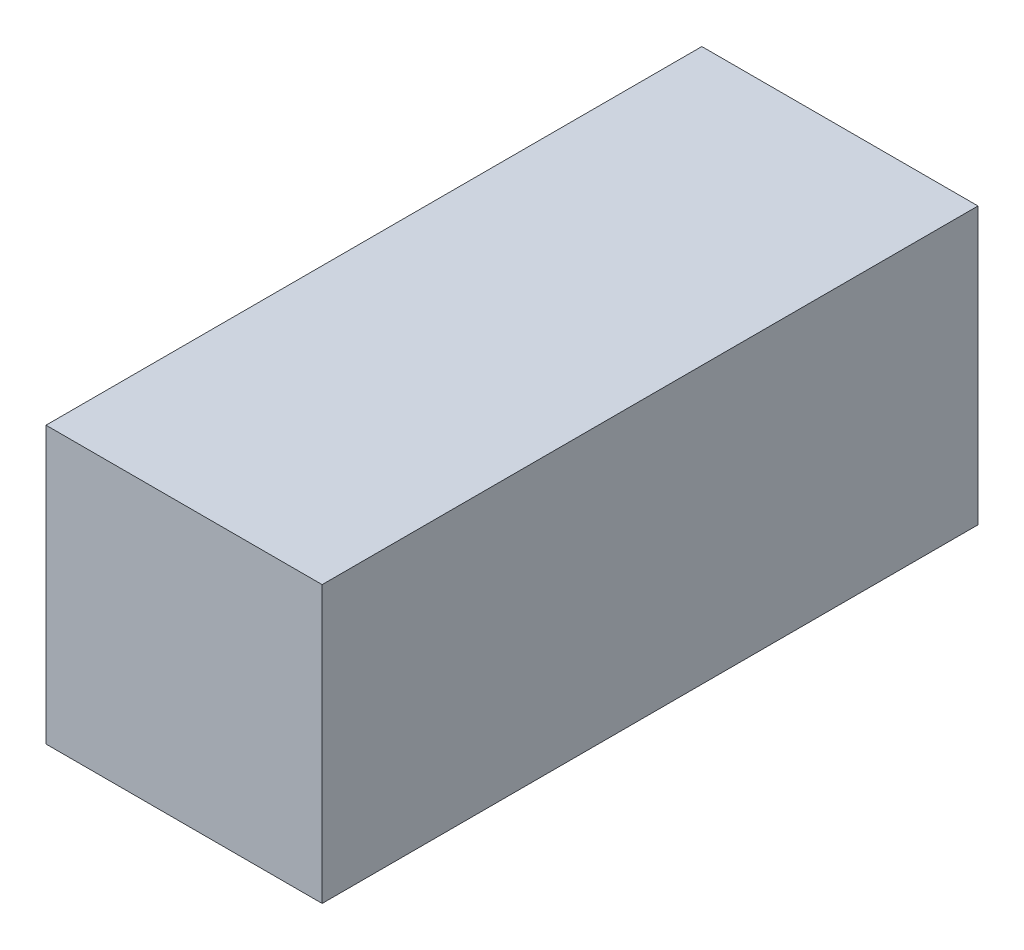
SolidWorks part; units mm, degrees
material "Cast Alloy Steel"
ref_plane "Front Plane" through (0, 0, 0) normal (0, 0, 1) x (1, 0, 0)
ref_plane "Top Plane" through (0, 0, 0) normal (0, 1, 0) x (1, 0, 0)
ref_plane "Right Plane" through (0, 0, 0) normal (1, 0, 0) x (0, 0, -1)
sketch "Sketch1" plane through (0, 0, 0) normal (0, 0, 1) x (1, 0, 0)
  line L1 (-2, 2) -> (2, 2)
  line L2 (-2, 2) -> (-2, -2)
  line L3 (-2, -2) -> (2, -2)
  line L4 (2, 2) -> (2, -2)
  line L5 (-2, 2) -> (2, -2) construction
  line L6 (-2, -2) -> (2, 2) construction
  point P0 (0, 0)
  dimension "D1" = 4
extrude "Boss-Extrude1" add sketch "Sketch1" along normal blind 9.5
move or copy body "Body-Move/Copy1" [suppressed] bodies to move or copy 101
